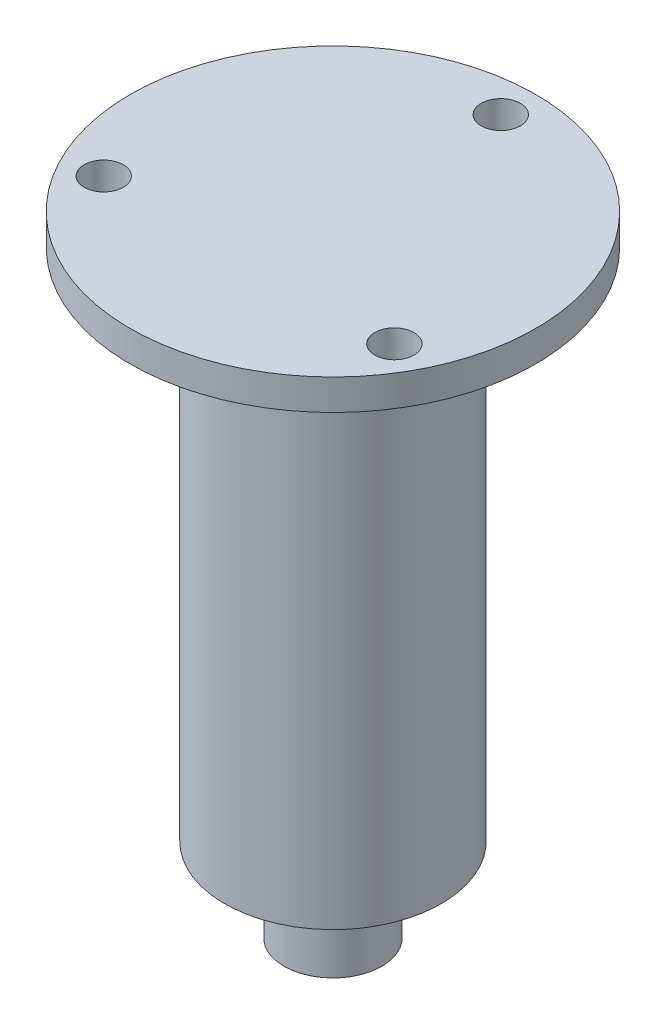
SolidWorks part; units mm, degrees
material "交联聚乙烯"
ref_plane "前视基准面" through (0, 0, 0) normal (0, 0, 1) x (1, 0, 0)
ref_plane "上视基准面" through (0, 0, 0) normal (0, 1, 0) x (1, 0, 0)
ref_plane "右视基准面" through (0, 0, 0) normal (1, 0, 0) x (0, 0, -1)
sketch "草图1" plane through (0, 0, 0) normal (0, 0, 1) x (1, 0, 0)
  line L0 (0, 0) -> (-3.5, 0)
  line L1 (-3.5, 0) -> (-3.5, 6)
  line L2 (-3.5, 6) -> (-7.75, 6)
  line L3 (-7.75, 6) -> (-7.75, 42.8)
  line L4 (-7.75, 42.8) -> (-14.5, 42.8)
  line L5 (-14.5, 42.8) -> (-14.5, 45)
  line L6 (-14.5, 45) -> (0, 45)
  line L7 (0, 45) -> (0, 0)
  point P3 (-0.1506, 0)
  dimension "D1" = 2.2
  dimension "D2" = 39
  dimension "D3" = 7.75
  dimension "D4" = 14.5
  dimension "D5" = 3.5
  dimension "D6" = 6
revolve "旋转1" add sketch "草图1" angle 360 about L7
sketch "草图2" plane through (0, 45, 0) normal (0, 1, 0) x (1, 0, 0)
  circle A0 centre (0, 12) radius 1.4
  circle A1 centre (10.3923, -6) radius 1.4
  circle A2 centre (-10.3923, -6) radius 1.4
  point P5 (11.7087, -5.4456)
  point P6 (0, 0)
  point P9 (0, 0)
  dimension "D2" = 2.8
  dimension "D1" = 12
  dimension "D3" = 3
extrude "切除-拉伸1" cut sketch "草图2" against normal through all
